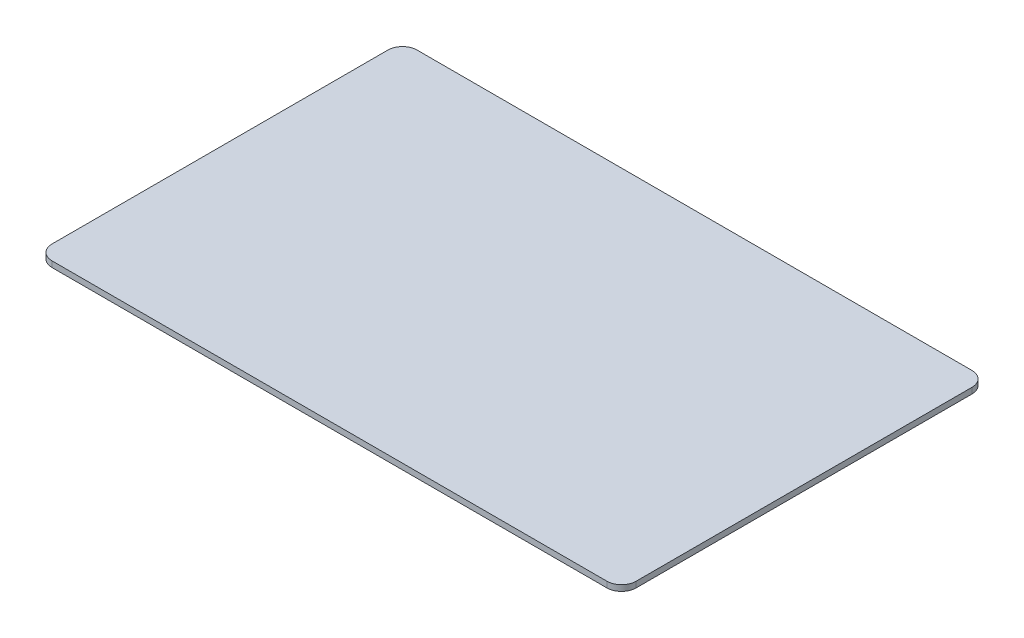
SolidWorks part; units mm, degrees
ref_plane "Ebene vorne" through (0, 0, 0) normal (0, 0, 1) x (1, 0, 0)
ref_plane "Ebene oben" through (0, 0, 0) normal (0, 1, 0) x (1, 0, 0)
ref_plane "Ebene rechts" through (0, 0, 0) normal (1, 0, 0) x (0, 0, -1)
sketch "Skizze1" plane through (0, 0, 0) normal (0, 1, 0) x (1, 0, 0)
  line L1 (4, 0) -> (156, 0)
  line L2 (0, 4) -> (0, 96)
  line L3 (4, 100) -> (156, 100)
  line L4 (160, 4) -> (160, 96)
  arc A0 (156, 100) -> (160, 96) centre (156, 96) cw
  arc A1 (156, 0) -> (160, 4) centre (156, 4) ccw
  arc A2 (4, 0) -> (0, 4) centre (4, 4) cw
  arc A3 (0, 96) -> (4, 100) centre (4, 96) cw
  point P9 (160, 0)
  point P12 (0, 0)
  point P15 (0, 100)
  dimension "D3" = 4
  dimension "D1" = 160
  dimension "D2" = 100
extrude "Aufsatz-Linear austragen1" add sketch "Skizze1" along normal blind 1.6
